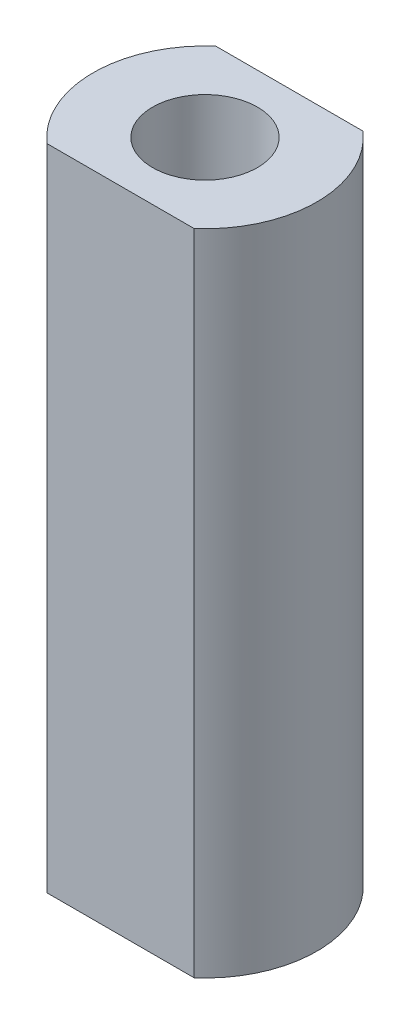
SolidWorks part; units mm, degrees
ref_plane "前基準面" through (0, 0, 0) normal (0, 0, 1) x (1, 0, 0)
ref_plane "上基準面" through (0, 0, 0) normal (0, 1, 0) x (1, 0, 0)
ref_plane "右基準面" through (0, 0, 0) normal (1, 0, 0) x (0, 0, -1)
sketch "草圖1" plane through (0, 0, 0) normal (0, 1, 0) x (1, 0, 0)
  circle A0 centre (0, 0) radius 9.7
  dimension "D1" = 19.4
extrude "伸長-薄件1" add sketch "草圖1" along normal blind 109.5 thin
ref_plane "平面1" through (0, 110, 0) normal (0, 1, 0) x (1, 0, 0)
sketch "草圖2" plane through (0, 110, 0) normal (0, 1, 0) x (1, 0, 0)
  line L1 (-22.7899, 15.6074) -> (22.7899, 15.6074)
  line L2 (-22.7899, 15.6074) -> (-22.7899, -15.6074)
  line L3 (-22.7899, -15.6074) -> (22.7899, -15.6074)
  line L4 (22.7899, 15.6074) -> (22.7899, -15.6074)
  line L5 (0, -15.6074) -> (0, 15.6074) construction
  line L6 (-22.7899, 0) -> (22.7899, 0) construction
  point P0 (0, 0)
extrude "填料-伸長1" add sketch "草圖2" along normal blind 10 and the other way blind 1
sketch "草圖3" plane through (0, 0, 0) normal (0, -1, 0) x (1, 0, 0)
  circle A0 centre (0, 0) radius 9.7
extrude "除料-伸長1" cut sketch "草圖3" against normal through all
sketch "草圖4" plane through (0, 109.5, 0) normal (0, 1, 0) x (1, 0, 0)
  line L1 (25.275, -22.6384) -> (-22.7899, -22.6384)
  line L2 (25.275, -22.6384) -> (25.275, -15.6074)
  line L3 (25.275, -15.6074) -> (-22.7899, -15.6074)
  line L4 (-22.7899, -22.6384) -> (-22.7899, -15.6074)
extrude "除料-伸長2" cut sketch "草圖4" against normal through all
sketch "草圖5" plane through (0, 0, 0) normal (0, -1, 0) x (1, 0, 0)
  circle A0 centre (0, 0) radius 20.7
extrude "除料-伸長-薄件1" cut sketch "草圖5" against normal through all thin
